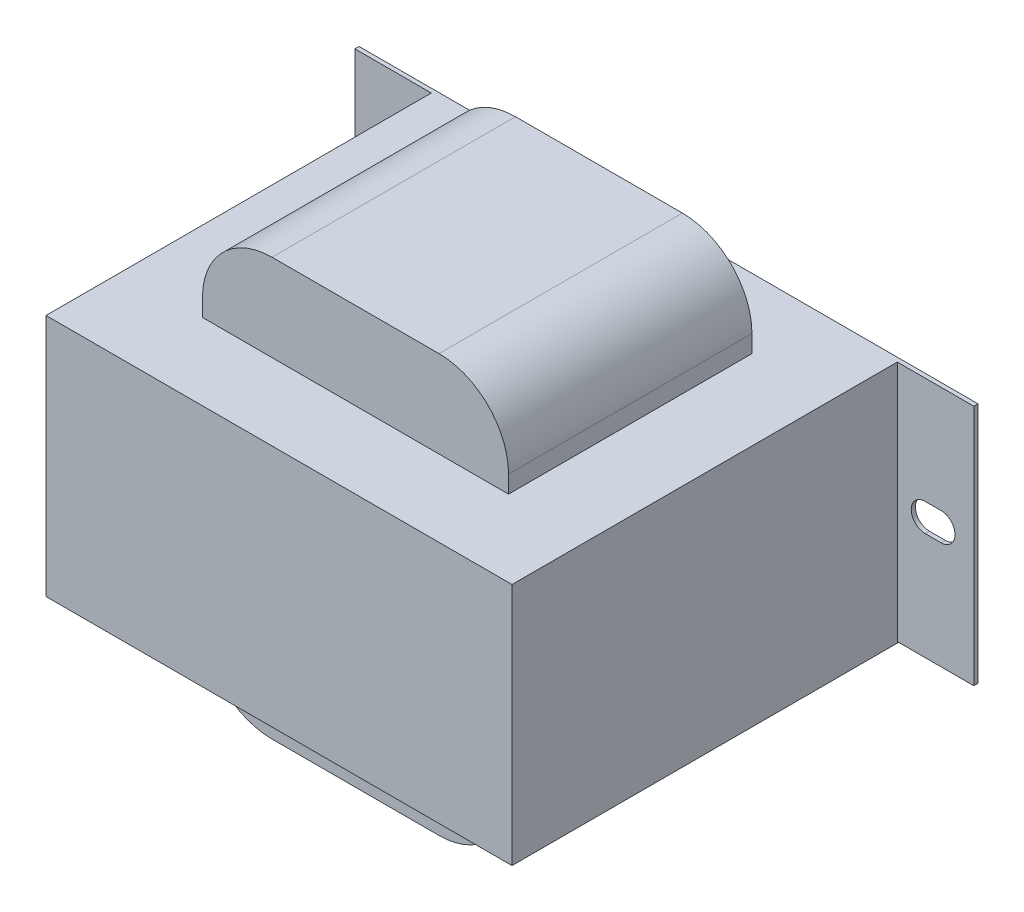
SolidWorks part; units mm, degrees
ref_plane "前视基准面" through (0, 0, 0) normal (0, 0, 1) x (1, 0, 0)
ref_plane "上视基准面" through (0, 0, 0) normal (0, 1, 0) x (1, 0, 0)
ref_plane "右视基准面" through (0, 0, 0) normal (1, 0, 0) x (0, 0, -1)
sketch "草图1" plane through (0, 0, 0) normal (0, 0, 1) x (1, 0, 0)
  line L0 (0, 78.0676) -> (0, -98.3955) construction
  line L1 (-33.5, 17.5) -> (33.5, 17.5)
  line L2 (-33.5, 17.5) -> (-33.5, -17.5)
  line L3 (-33.5, -17.5) -> (33.5, -17.5)
  line L4 (33.5, 17.5) -> (33.5, -17.5)
  line L5 (-98.6118, 0) -> (97.7467, 0) construction
  dimension "D1" = 35
  dimension "D2" = 67
extrude "拉伸1" add sketch "草图1" along normal blind 56
sketch "草图2" plane through (0, 0, 56) normal (0, 0, 1) x (1, 0, 0)
  line L1 (-12, 30) -> (12, 30)
  line L2 (-22, 20) -> (-22, -20)
  line L3 (-12, -30) -> (12, -30)
  line L4 (22, 20) -> (22, -20)
  arc A0 (-12, 30) -> (-22, 20) centre (-12, 20) ccw
  arc A1 (12, 30) -> (22, 20) centre (12, 20) cw
  arc A2 (-22, -20) -> (-12, -30) centre (-12, -20) ccw
  arc A3 (12, -30) -> (22, -20) centre (12, -20) ccw
  point P4 (0, 30)
  point P6 (-22, 0)
  point P9 (-22, 30)
  point P12 (22, 30)
  point P17 (22, -30)
  dimension "D3" = 10
  dimension "D1" = 44
  dimension "D2" = 60
extrude "拉伸2" add sketch "草图2" against normal blind 35 from offset 11
sketch "草图3" plane through (0, 0, 0) normal (0, 0, -1) x (-1, 0, 0)
  line L0 (-39.8, 2.1472) -> (-37.5, 2.1472)
  line L1 (-33.5, 17.5) -> (-44.5, 17.5)
  line L2 (-33.5, 17.5) -> (-33.5, -17.3083)
  line L3 (-33.5, -17.3083) -> (-44.5, -17.3083)
  line L4 (-44.5, 17.5) -> (-44.5, -17.3083)
  line L5 (33.5, 17.5) -> (44.5, 17.5)
  line L6 (33.5, 17.5) -> (33.5, -17.3083)
  line L7 (33.5, -17.3083) -> (44.5, -17.3083)
  line L8 (44.5, 17.5) -> (44.5, -17.3083)
  line L9 (-37.5, -1.8528) -> (-39.8, -1.8528)
  line L10 (0, 41.9816) -> (0, -49.4729) construction
  line L11 (37.5, -1.8528) -> (39.8, -1.8528)
  line L12 (39.8, 2.1472) -> (37.5, 2.1472)
  arc A0 (-39.8, 2.1472) -> (-39.8, -1.8528) centre (-39.8, 0.1472) ccw
  arc A1 (-37.5, -1.8528) -> (-37.5, 2.1472) centre (-37.5, 0.1472) ccw
  arc A2 (37.5, -1.8528) -> (37.5, 2.1472) centre (37.5, 0.1472) cw
  arc A3 (39.8, 2.1472) -> (39.8, -1.8528) centre (39.8, 0.1472) cw
  dimension "D3" = 4
  dimension "D4" = 2.3
  dimension "D5" = 4.7
  dimension "D1" = 11
  dimension "D2" = 11
extrude "拉伸3" add sketch "草图3" against normal blind 0.6
